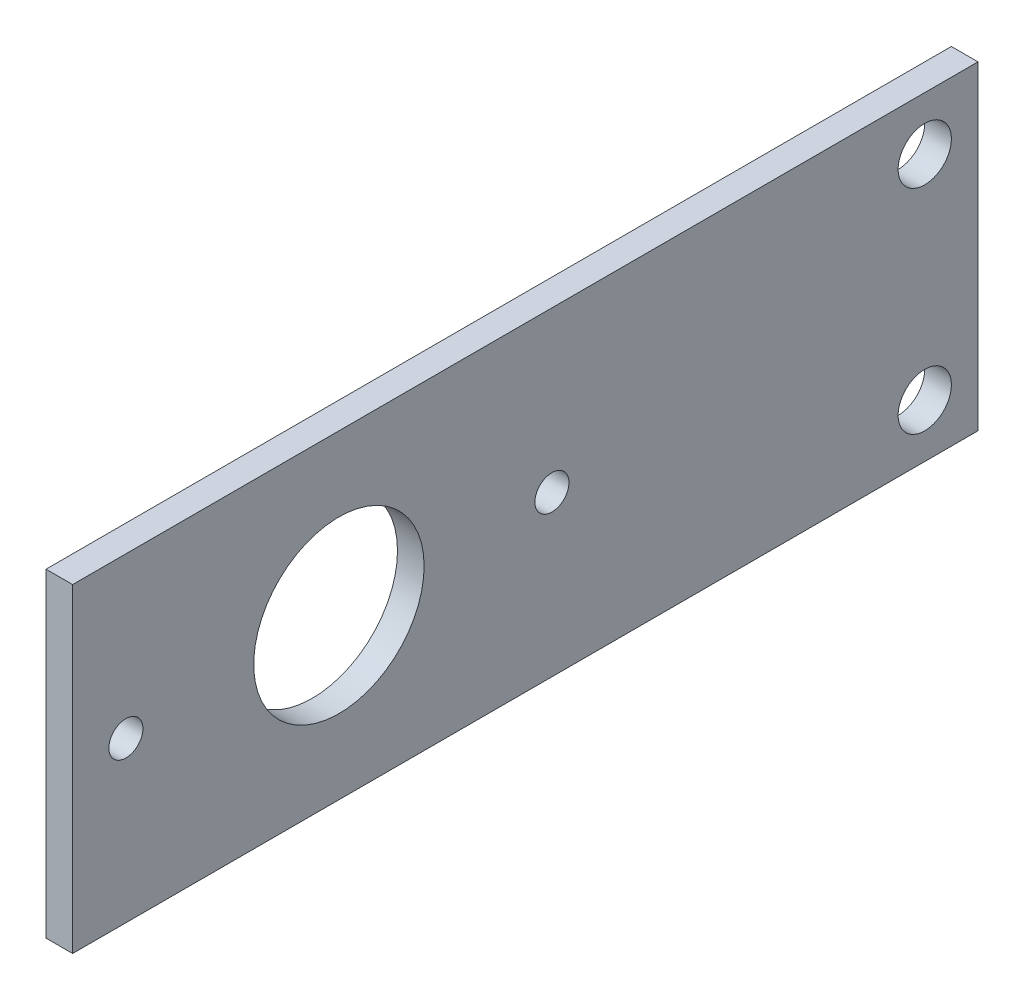
SolidWorks part; units mm, degrees
ref_plane "FRONT" through (0, 0, 0) normal (0, 0, 1) x (1, 0, 0)
ref_plane "TOP" through (0, 0, 0) normal (0, 1, 0) x (1, 0, 0)
ref_plane "RIGHT" through (0, 0, 0) normal (1, 0, 0) x (0, 0, -1)
sketch "Sketch1" plane through (0, 0, 0) normal (1, 0, 0) x (0, 0, -1)
  line L1 (0, 0) -> (-107.95, 0)
  line L2 (0, 0) -> (0, 38.1)
  line L3 (0, 38.1) -> (-107.95, 38.1)
  line L4 (-107.95, 0) -> (-107.95, 38.1)
  circle A0 centre (-6.35, 31.75) radius 3.175
  circle A1 centre (-6.35, 6.35) radius 3.175
  circle A2 centre (-50.8, 19.05) radius 2.032
  circle A3 centre (-76.2, 19.05) radius 10.16
  circle A4 centre (-101.6, 19.05) radius 2.032
  dimension "D4" = 6.35
  dimension "D5" = 6.35
  dimension "D8" = 6.35
  dimension "D10" = 4.064
  dimension "D14" = 20.32
  dimension "D16" = 4.064
  dimension "D1" = 107.95
  dimension "D2" = 38.1
  dimension "D3" = 25.4
  dimension "D6" = 6.35
  dimension "D7" = 6.35
  dimension "D9" = 19.05
  dimension "D11" = 6.35
  dimension "D12" = 25.4
  dimension "D13" = 19.05
  dimension "D15" = 50.8
  dimension "D17" = 19.05
extrude "Boss-Extrude1" add sketch "Sketch1" along normal blind 3.175
